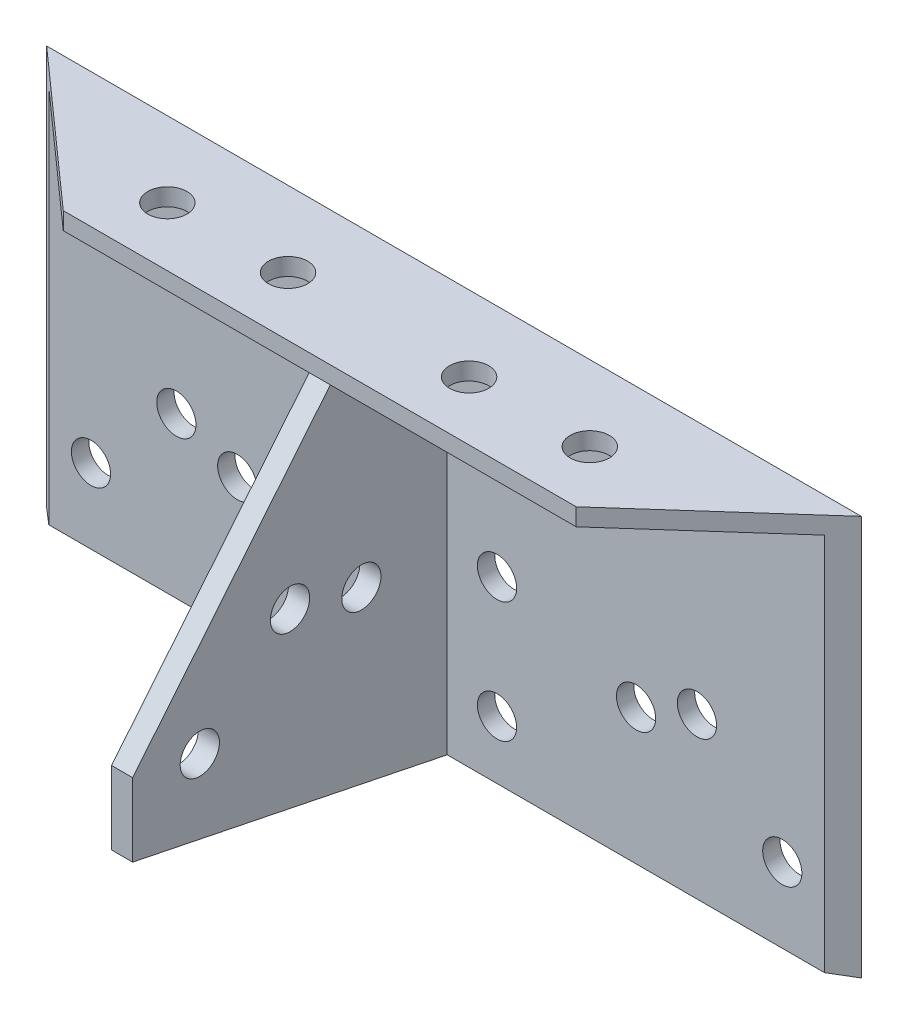
SolidWorks part; units mm, degrees
ref_plane "前视" through (0, 0, 0) normal (0, 0, 1) x (1, 0, 0)
ref_plane "上视" through (0, 0, 0) normal (0, 1, 0) x (1, 0, 0)
ref_plane "右视" through (0, 0, 0) normal (1, 0, 0) x (0, 0, -1)
sketch "草图1" plane through (0, 0, 0) normal (0, 0, 1) x (1, 0, 0)
  line L0 (270, 425.0457) -> (270, -284.5347) construction
  line L1 (0, 0) -> (540, 0)
  line L2 (0, 0) -> (0, 265)
  line L3 (0, 265) -> (540, 265)
  line L4 (540, 0) -> (540, 265)
  line L5 (270, 281) -> (-106.4291, -95.4291) construction
  line L6 (230, 208.0498) -> (230, 33.9502) construction
  line L7 (270, 147.3) -> (40.8974, 51.8974) construction
  circle A0 centre (97.4659, 108.4659) radius 13
  circle A1 centre (40.8974, 51.8974) radius 13
  circle A2 centre (499.1026, 51.8974) radius 13
  circle A3 centre (402.171, 92.2615) radius 13
  circle A4 centre (230, 121) radius 13
  circle A5 centre (230, 41) radius 13
  circle A6 centre (310, 41) radius 13
  circle A7 centre (310, 121) radius 13
  circle A8 centre (137.829, 92.2615) radius 13
  circle A9 centre (442.5341, 108.4659) radius 13
  point P7 (270, 281)
  point P28 (270, 147.3)
  dimension "D5" = 26
  dimension "D1" = 265
  dimension "D2" = 540
  dimension "D3" = 16
  dimension "D4" = 45
  dimension "D6" = 244
  dimension "D7" = 80
  dimension "D8" = 40
  dimension "D9" = 41
  dimension "D10" = 80
  dimension "D11" = 133.7
  dimension "D12" = 105
extrude "基体-拉伸" add sketch "草图1" along normal blind 11.5
sketch "草图2" plane through (0, 0, 11.5) normal (0, 0, 1) x (1, 0, 0)
  line L1 (540, 0) -> (540, 265) construction
  line L2 (0, 265) -> (540, 265)
  line L3 (0, 265) -> (0, 253.5)
  line L4 (0, 253.5) -> (540, 253.5)
  line L5 (540, 265) -> (540, 253.5)
  dimension "D1" = 11.5
extrude "凸台-拉伸1" add sketch "草图2" along normal blind 77.5
sketch "草图3" plane through (0, 265, 0) normal (0, 1, 0) x (-1, 0, 0)
  line L0 (-540, 89) -> (0, 89) construction
  line L1 (0, 89) -> (0, 0) construction
  line L2 (-270, -68.7135) -> (-270, 185.0878) construction
  line L3 (-540, 89) -> (-540, 0) construction
  line L4 (0, 0) -> (-100, 89)
  line L5 (-540, 0) -> (-440, 89)
  line L6 (0, 0) -> (0, 89)
  line L7 (0, 89) -> (-100, 89)
  line L8 (-540, 89) -> (-440, 89)
  line L9 (-540, 0) -> (-540, 89)
  point P0 (-100, 89)
  dimension "D1" = 100
extrude "切除-拉伸1" cut sketch "草图3" against normal through all
sketch "草图4" plane through (0, 265, 0) normal (0, 1, 0) x (-1, 0, 0)
  line L0 (-270, -67.5439) -> (-270, 192.1053) construction
  line L1 (-540, 0) -> (-440, 89) construction
  line L2 (-100, 89) -> (0, 0) construction
  line L3 (0, 50) -> (-540, 50) construction
  line L4 (-540, 0) -> (0, 0) construction
  circle A0 centre (-210, 50) radius 13
  circle A1 centre (-130, 50) radius 13
  circle A2 centre (-410, 50) radius 13
  circle A3 centre (-330, 50) radius 13
  dimension "D2" = 26
  dimension "D1" = 50
  dimension "D3" = 60
  dimension "D4" = 80
extrude "切除-拉伸2" cut sketch "草图4" against normal through all
sketch "草图5" plane through (0, 0, 11.5) normal (0, 0, 1) x (1, 0, 0)
  line L0 (270, 315.5409) -> (270, -66.9152) construction
  line L1 (527.0787, 0) -> (527.0787, 253.5) construction
  line L2 (12.9213, 253.5) -> (12.9213, 0) construction
  line L3 (100, 253.5) -> (440, 253.5) construction
  line L4 (263, 253.5) -> (277, 253.5)
  line L5 (263, 253.5) -> (263, 0)
  line L6 (263, 0) -> (277, 0)
  line L7 (277, 253.5) -> (277, 0)
  line L8 (12.9213, 0) -> (527.0787, 0) construction
  dimension "D1" = 14
extrude "凸台-拉伸2" add sketch "草图5" along normal blind 208.5
sketch "草图6" plane through (277, 0, 0) normal (1, 0, 0) x (0, 0, -1)
  line L0 (45, 281) -> (45, -17.4312) construction
  line L1 (0, 0) -> (0, 265) construction
  line L2 (0, 265) -> (-89, 265) construction
  line L3 (45, 281) -> (-517.5, -219) construction
  line L4 (-220, 0) -> (-220, 253.5) construction
  line L5 (-89, 253.5) -> (-220, 93.5)
  line L6 (-220, 93.5) -> (-220, 253.5)
  line L7 (-220, 253.5) -> (-89, 253.5)
  line L8 (-175.4857, 85.0127) -> (115.3784, 198.8898) construction
  line L13 (-220, 0) -> (-11.5, 0) construction
  line L14 (-220, 45) -> (0, 0)
  line L15 (0, 0) -> (-220, 0)
  line L16 (-220, 0) -> (-220, 45)
  circle A0 centre (-115.693, 138.1618) radius 13
  circle A1 centre (-175.4857, 85.0127) radius 13
  circle A2 centre (-68.4004, 126.938) radius 13
  point P4 (45, 281)
  point P13 (-220, 93.5)
  point P21 (-220, 45)
  dimension "D4" = 26
  dimension "D1" = 45
  dimension "D2" = 16
  dimension "D3" = 562.5
  dimension "D5" = 215
  dimension "D6" = 80
  dimension "D7" = 160
  dimension "D8" = 45
  dimension "D9" = 21.381
  dimension "D10" = 115
  dimension "D11" = 500
extrude "切除-拉伸3" cut sketch "草图6" against normal through all
sketch "草图7" plane through (277, 0, 0) normal (-1, 0, 0) x (0, 0, 1)
  line L0 (0, 0) -> (11.5, 2.3523)
  line L1 (11.5, 2.3523) -> (11.5, 0)
  line L2 (11.5, 0) -> (0, 0)
extrude "切除-拉伸4" cut sketch "草图7" against normal through all
